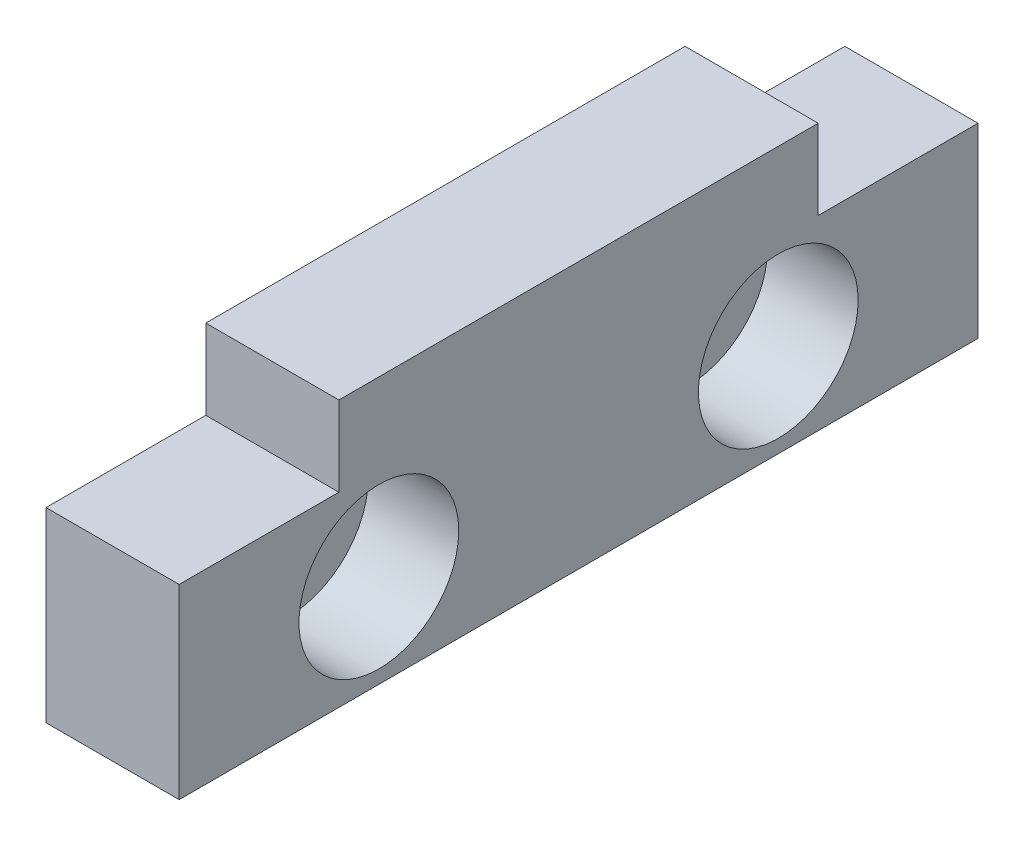
SolidWorks part; units mm, degrees
material "45#"
ref_plane "前视" through (0, 0, 0) normal (0, 0, 1) x (1, 0, 0)
ref_plane "上视" through (0, 0, 0) normal (0, 1, 0) x (1, 0, 0)
ref_plane "右视" through (0, 0, 0) normal (1, 0, 0) x (0, 0, -1)
sketch "草图1" plane through (0, 0, 0) normal (1, 0, 0) x (0, 0, -1)
  line L1 (-15, -5) -> (15, -5)
  line L2 (-15, -5) -> (-15, 5)
  line L3 (-15, 5) -> (15, 5)
  line L4 (15, -5) -> (15, 5)
  line L5 (-15, -5) -> (15, 5) construction
  line L6 (-15, 5) -> (15, -5) construction
  point P0 (0, 0)
  dimension "D1" = 30
  dimension "D2" = 10
extrude "凸台-拉伸1" add sketch "草图1" along normal blind 5
sketch "草图4" plane through (5, 0, 0) normal (1, 0, 0) x (0, 0, -1)
  line L0 (0, 5) -> (0, -5) construction
  line L1 (15, 5) -> (-15, 5) construction
  line L2 (-15, -5) -> (15, -5) construction
  line L3 (9, 5) -> (9, 2)
  line L4 (-15, 5) -> (-9, 5)
  line L5 (-15, 5) -> (-15, 2)
  line L6 (-15, 2) -> (-9, 2)
  line L7 (-9, 5) -> (-9, 2)
  line L8 (15, 2) -> (9, 2)
  line L9 (15, 5) -> (15, 2)
  line L10 (15, 5) -> (9, 5)
  dimension "D1" = 18
  dimension "D2" = 7
extrude "切除-拉伸1" cut sketch "草图4" against normal through all
hole_wizard "打孔尺寸根据内六角圆柱头螺钉的类型1" positions "草图3" profile "草图2" counterbore size "M3" standard "Gb" end condition through all
sketch "草图3" plane through (5, 0, 0) normal (1, 0, 0) x (0, 0, -1)
  line L0 (-15, -1.5) -> (0, -1.5) construction
  line L2 (0, -1.5) -> (0, 5) construction
  line L3 (9, 5) -> (-9, 5) construction
  line L5 (-15, 2) -> (-15, -5) construction
  point P0 (-7.5, -1.5)
  point P15 (7.5, -1.5)
  dimension "D1" = 15
sketch "草图2" plane through (5, -1.5, 7.5) normal (0, 1, 0) x (0, 0, -1)
  line L0 (0, 0) -> (0, 5)
  line L1 (0, 5) -> (1.7, 5)
  line L3 (1.7, 5) -> (1.7, 3.4)
  line L4 (1.7, 3.4) -> (3, 3.4)
  line L5 (3, 3.4) -> (3, 0)
  line L7 (3, 0) -> (0, 0)
  line L11 (0, -6.35) -> (0, 107.95) construction
  dimension "通孔孔直径" = 3.4
  dimension "通孔孔深度" = 5
  dimension "柱形沉头孔直径" = 6
  dimension "柱形沉头孔深度" = 3.4
